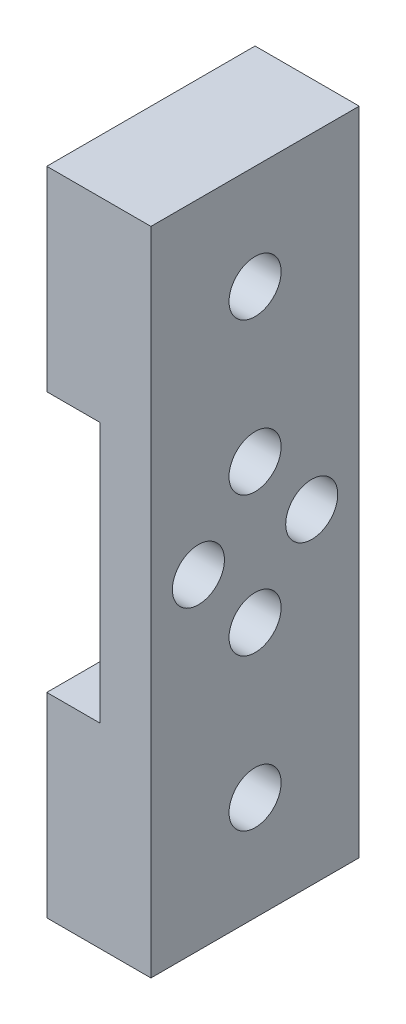
SolidWorks part; units mm, degrees
ref_plane "Front Plane" through (0, 0, 0) normal (0, 0, 1) x (1, 0, 0)
ref_plane "Top Plane" through (0, 0, 0) normal (0, 1, 0) x (1, 0, 0)
ref_plane "Right Plane" through (0, 0, 0) normal (1, 0, 0) x (0, 0, -1)
sketch "Sketch1" plane through (0, 0, 0) normal (0, 0, 1) x (1, 0, 0)
  line L0 (0, 39.6875) -> (0, 15.875)
  line L1 (0, -39.6875) -> (12.7, -39.6875)
  line L2 (12.7, -39.6875) -> (12.7, 39.6875)
  line L3 (12.7, 39.6875) -> (0, 39.6875)
  line L4 (0, -15.875) -> (0, -39.6875)
  line L5 (0, 15.875) -> (6.477, 15.875)
  line L7 (0, -15.875) -> (6.477, -15.875)
  line L8 (6.477, 15.875) -> (6.477, -15.875)
  point P2 (6.477, 0)
  dimension "D1" = 12.7
  dimension "D2" = 79.375
  dimension "D3" = 31.75
  dimension "D4" = 6.477
  dimension "D5" = 23.8125
extrude "Boss-Extrude1" add sketch "Sketch1" along normal mid plane 25.4
sketch "Sketch2" plane through (0, 0, 0) normal (-1, 0, 0) x (0, 0, 1)
  line L2 (-12.7, 39.6875) -> (-12.7, 15.875) construction
  line L4 (12.7, 39.6875) -> (-12.7, 39.6875) construction
  circle A1 centre (0, 26.9875) radius 3.175
  dimension "D3" = 6.35
  dimension "D1" = 12.7
  dimension "D2" = 12.7
extrude "Cut-Extrude1" cut sketch "Sketch2" against normal up to next contours A1
mirror "Mirror1" about plane through (0, 0, 0) normal (0, 1, 0) of "Cut-Extrude1"
sketch "Sketch3" plane through (6.477, 0, 0) normal (-1, 0, 0) x (0, 0, 1)
  line L0 (-6.9088, 0) -> (0, 0) construction
  line L1 (12.7, -39.6875) -> (-12.7, -39.6875) construction
  line L2 (0, 0) -> (6.9088, 0.0125) construction
  circle A0 centre (0, 8.4963) radius 3.175
  circle A1 centre (0, -8.4963) radius 3.175
  circle A2 centre (6.9088, 0.0125) radius 3.175
  circle A3 centre (-6.9088, 0) radius 3.175
  dimension "D5" = 6.35
  dimension "D1" = 39.7
  dimension "D2" = 48.1838
  dimension "D3" = 16.9926
  dimension "D4" = 13.8176
extrude "Cut-Extrude2" cut sketch "Sketch3" against normal up to next
